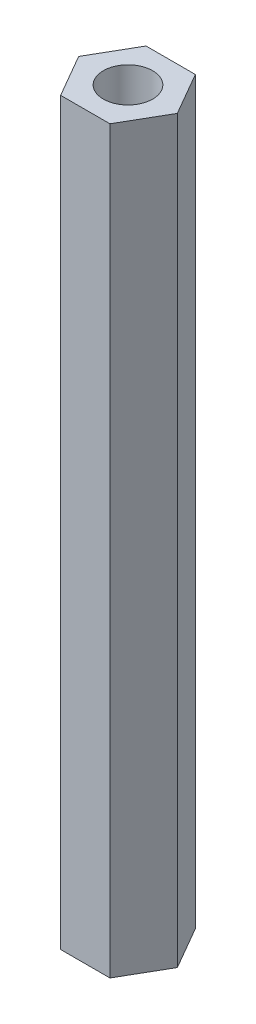
SolidWorks part; units mm, degrees
ref_plane "前视基准面" through (0, 0, 0) normal (0, 0, 1) x (1, 0, 0)
ref_plane "上视基准面" through (0, 0, 0) normal (0, 1, 0) x (1, 0, 0)
ref_plane "右视基准面" through (0, 0, 0) normal (1, 0, 0) x (0, 0, -1)
sketch "草图1" plane through (0, 0, 0) normal (0, 1, 0) x (1, 0, 0)
  line L0 (-1.9018, 4.3296) -> (2.0982, 4.3296)
  line L1 (2.0982, 4.3296) -> (4.0982, 0.8655)
  line L2 (4.0982, 0.8655) -> (2.0982, -2.5986)
  line L3 (2.0982, -2.5986) -> (-1.9018, -2.5986)
  line L4 (-1.9018, -2.5986) -> (-3.9018, 0.8655)
  line L5 (-3.9018, 0.8655) -> (-1.9018, 4.3296)
  line L6 (-3.9018, 0.8655) -> (4.0982, 0.8655)
  line L7 (-1.9018, 4.3296) -> (2.0982, -2.5986)
  circle A1 centre (0.0982, 0.8655) radius 2
  dimension "D5" = 4
  dimension "D1" = 120
  dimension "D2" = 120
  dimension "D3" = 120
  dimension "D4" = 120
  dimension "D6" = 4
  dimension "D7" = 4
  dimension "D8" = 4
  dimension "D9" = 4
extrude "凸台-拉伸1" add sketch "草图1" along normal blind 60 contours A1 L6 L1 L0 L7 | A1 L7 L5 L6 | A1 L6 L4 L3 L7 | A1 L7 L2 L6
